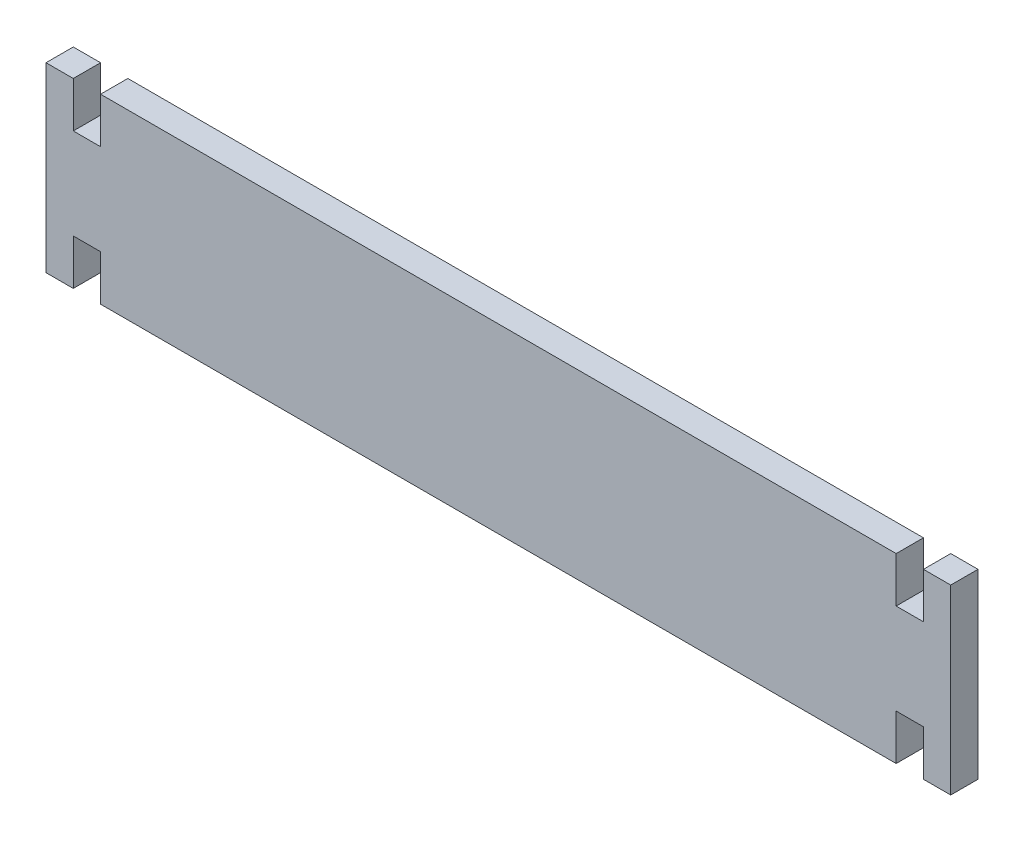
SolidWorks part; units mm, degrees
ref_plane "Front" through (0, 0, 0) normal (0, 0, 1) x (1, 0, 0)
ref_plane "Top" through (0, 0, 0) normal (0, 1, 0) x (1, 0, 0)
ref_plane "Right" through (0, 0, 0) normal (1, 0, 0) x (0, 0, -1)
sketch "Sketch1" plane through (0, 0, 0) normal (0, 0, 1) x (1, 0, 0)
  line L1 (0, 0) -> (-199, 0)
  line L2 (0, 0) -> (0, 40)
  line L3 (0, 40) -> (-199, 40)
  line L4 (-199, 0) -> (-199, 40)
  dimension "D1" = 40
  dimension "D2" = 199
extrude "Boss-Extrude1" add sketch "Sketch1" along normal blind 6
sketch "Sketch2" plane through (0, 0, 6) normal (0, 0, 1) x (1, 0, 0)
  line L0 (0, 40) -> (-199, 40) construction
  line L1 (-193, 40) -> (-187, 40)
  line L2 (-193, 40) -> (-193, 30)
  line L3 (-193, 30) -> (-187, 30)
  line L4 (-187, 40) -> (-187, 30)
  line L5 (-199, 40) -> (-199, 0) construction
  dimension "D1" = 10
  dimension "D2" = 6
  dimension "D3" = 6
extrude "Cut-Extrude1" cut sketch "Sketch2" against normal through all
pattern_linear "LPattern1" count 2 spacing 181 along (1, 0, 0) count 2 spacing 30 along (0, -1, 0) of "Cut-Extrude1"
